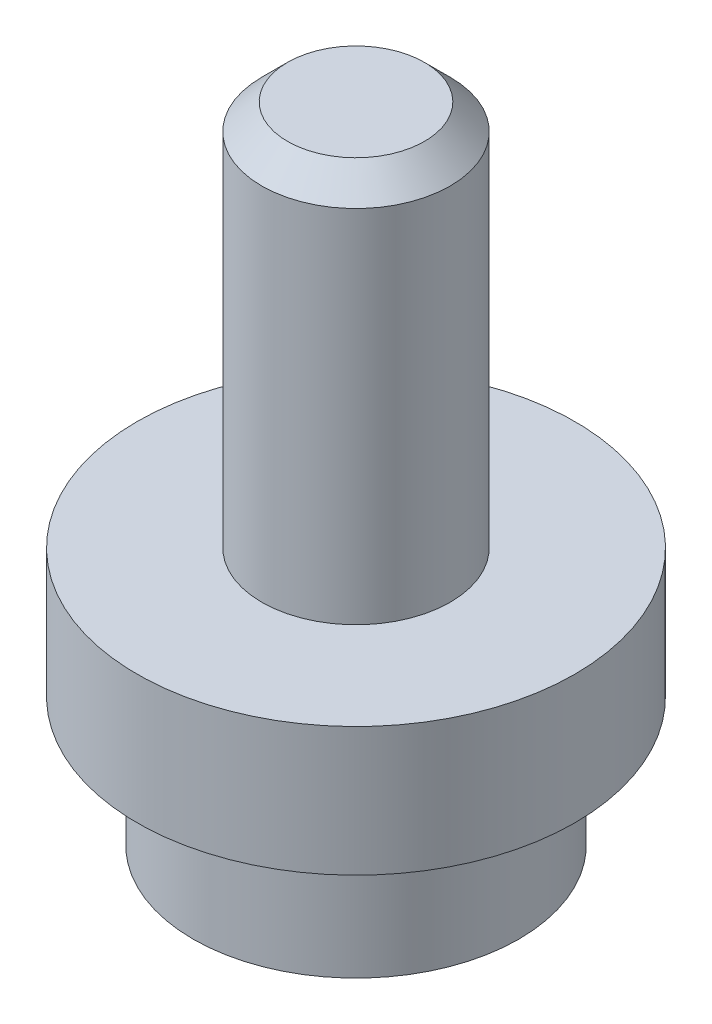
SolidWorks part; units mm, degrees
ref_plane "前视基准面" through (0, 0, 0) normal (0, 0, 1) x (1, 0, 0)
ref_plane "上视基准面" through (0, 0, 0) normal (0, 1, 0) x (1, 0, 0)
ref_plane "右视基准面" through (0, 0, 0) normal (1, 0, 0) x (0, 0, -1)
sketch "草图1" plane through (0, 0, 0) normal (0, 0, 1) x (1, 0, 0)
  line L0 (0, 0) -> (6.325, 0)
  line L1 (6.325, 0) -> (6.325, 5)
  line L2 (6.325, 5) -> (8.5, 5)
  line L3 (8.5, 5) -> (8.5, 10)
  line L4 (8.5, 10) -> (3.66, 10)
  line L5 (3.66, 10) -> (3.66, 25)
  line L6 (3.66, 25) -> (0, 25)
  line L7 (0, 25) -> (0, 0)
  line L8 (0, 25) -> (0, 35.7718) construction
  dimension "D1" = 10
  dimension "D2" = 5
  dimension "D3" = 25
  dimension "D4" = 12.65
  dimension "D5" = 17
  dimension "D6" = 7.32
revolve "旋转1" add sketch "草图1" angle 360 about L8
chamfer "倒角1" distance 1 angle 45 1 edges at (3.66, 25, 0)
